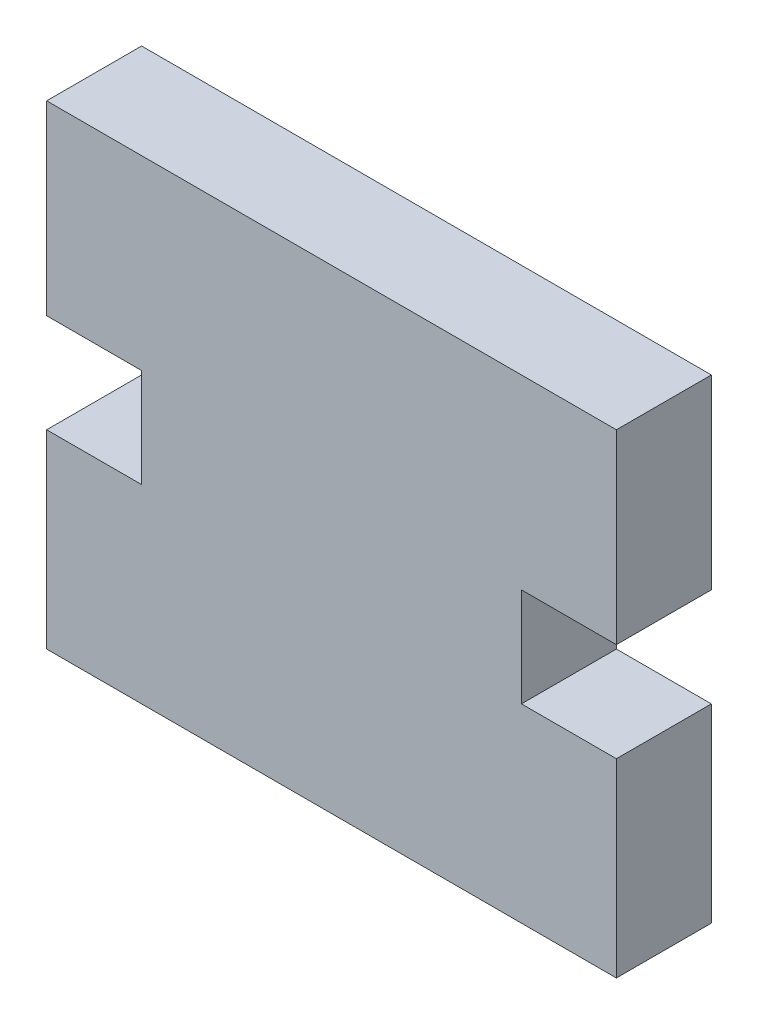
SolidWorks part; units mm, degrees
ref_plane "Front Plane" through (0, 0, 0) normal (0, 0, 1) x (1, 0, 0)
ref_plane "Top Plane" through (0, 0, 0) normal (0, 1, 0) x (1, 0, 0)
ref_plane "Right Plane" through (0, 0, 0) normal (1, 0, 0) x (0, 0, -1)
sketch "Sketch1" plane through (0, 0, 0) normal (0, 0, 1) x (1, 0, 0)
  line L21 (10, 2.7) -> (15, 2.7)
  line L23 (15, -2.5) -> (15, -12.5)
  line L24 (10, -2.5) -> (15, -2.5)
  line L25 (10, 2.7) -> (10, -2.5)
  line L26 (15, 12.5) -> (15, 2.7)
  line L27 (15, -12.5) -> (-15, -12.5)
  line L28 (0, -12.5) -> (0, -5) construction
  line L35 (15, 12.5) -> (-15, 12.5)
  line L36 (-15, 12.5) -> (-15, 2.7)
  line L37 (-10, 2.7) -> (-10, -2.5)
  line L38 (-10, -2.5) -> (-15, -2.5)
  line L39 (-15, -2.5) -> (-15, -12.5)
  line L40 (-10, 2.7) -> (-15, 2.7)
  point P4 (0, 12.5)
  point P5 (0, 12.5)
  dimension "D1" = 5.2
  dimension "D2" = 5
  dimension "D3" = 15
  dimension "D4" = 15
  dimension "D5" = 10
  dimension "D7" = 9.8
  dimension "D9" = 12.5
extrude "Boss-Extrude1" add sketch "Sketch1" along normal blind 5
